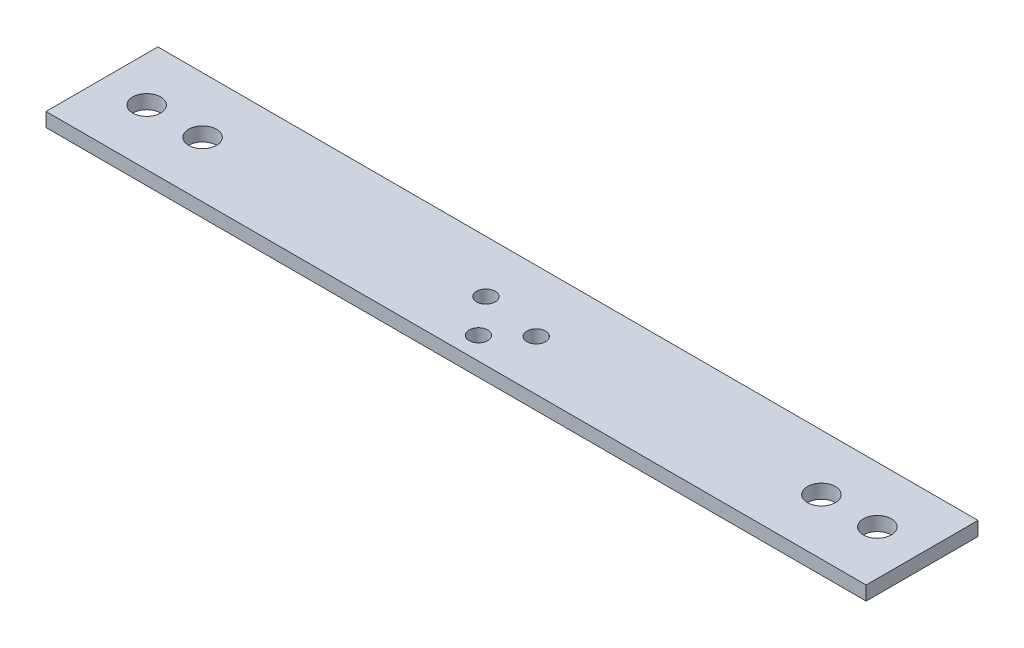
SolidWorks part; units mm, degrees
ref_plane "Front Plane" through (0, 0, 0) normal (0, 0, 1) x (1, 0, 0)
ref_plane "Top Plane" through (0, 0, 0) normal (0, 1, 0) x (1, 0, 0)
ref_plane "Right Plane" through (0, 0, 0) normal (1, 0, 0) x (0, 0, -1)
sketch "Sketch2" plane through (0, 0, 0) normal (0, 1, 0) x (1, 0, 0)
  line L1 (-139.7, -19.05) -> (139.7, -19.05)
  line L2 (-139.7, -19.05) -> (-139.7, 19.05)
  line L3 (-139.7, 19.05) -> (139.7, 19.05)
  line L4 (139.7, -19.05) -> (139.7, 19.05)
  line L5 (0, 19.05) -> (0, -19.05) construction
  line L6 (-139.7, 0) -> (139.7, 0) construction
  circle A0 centre (-124.46, 0) radius 4.7625
  circle A1 centre (-105.41, 0) radius 4.7625
  circle A2 centre (124.46, 0) radius 4.7625
  circle A3 centre (105.41, 0) radius 4.7625
  circle A4 centre (0, -11.43) radius 3.175
  circle A5 centre (-10.16, 1.27) radius 3.175
  circle A6 centre (10.16, -1.905) radius 3.175
  point P0 (0, 0)
  dimension "D3" = 9.525
  dimension "D6" = 6.35
  dimension "D1" = 38.1
  dimension "D2" = 279.4
  dimension "D4" = 19.05
  dimension "D5" = 15.24
  dimension "D7" = 7.62
  dimension "D8" = 20.32
  dimension "D9" = 17.145
  dimension "D10" = 10.16
  dimension "D11" = 10.16
extrude "Boss-Extrude1" add sketch "Sketch2" along normal blind 4.7625
